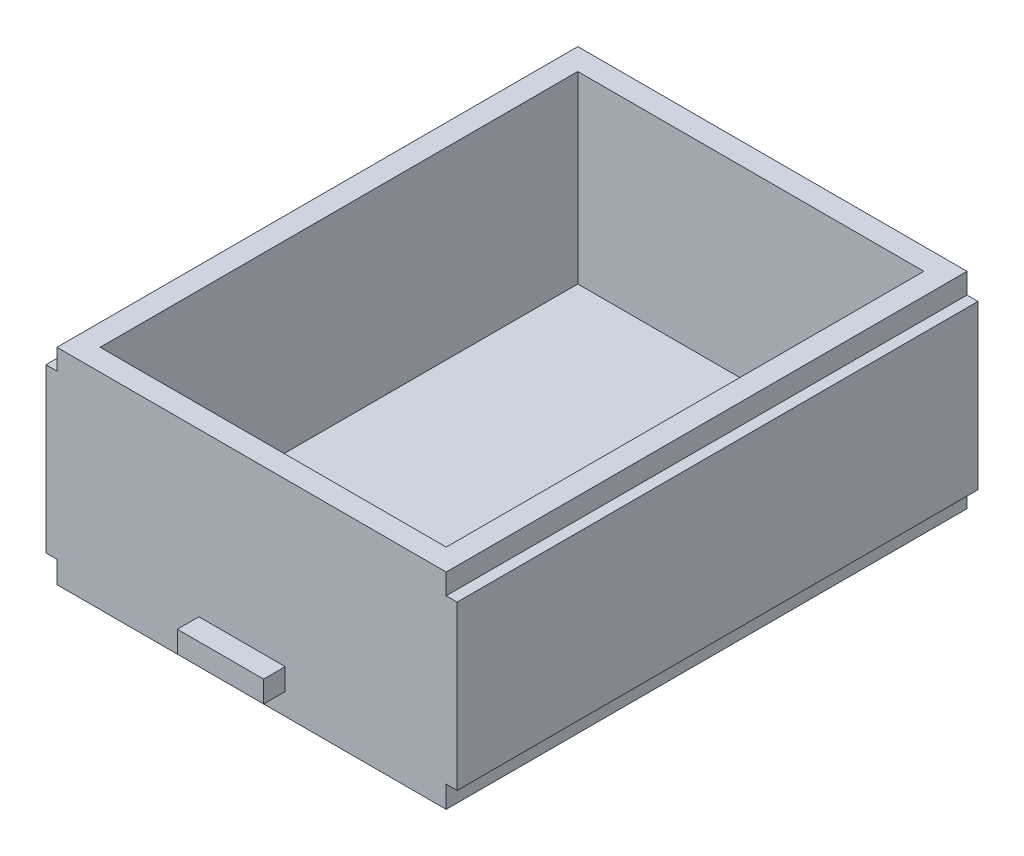
SolidWorks part; units mm, degrees
ref_plane "Alzado" through (0, 0, 0) normal (0, 0, 1) x (1, 0, 0)
ref_plane "Planta" through (0, 0, 0) normal (0, 1, 0) x (1, 0, 0)
ref_plane "Vista lateral" through (0, 0, 0) normal (1, 0, 0) x (0, 0, -1)
sketch "Croquis1" plane through (0, 0, 0) normal (0, 0, 1) x (1, 0, 0)
  line L1 (36.068, -19.05) -> (-36.068, -19.05)
  line L2 (36.068, -19.05) -> (36.068, 19.05)
  line L3 (36.068, 19.05) -> (-36.068, 19.05)
  line L4 (-36.068, -19.05) -> (-36.068, 19.05)
  line L5 (36.068, -19.05) -> (-36.068, 19.05) construction
  line L6 (36.068, 19.05) -> (-36.068, -19.05) construction
  point P0 (0, 0)
  dimension "D1" = 72.136
  dimension "D2" = 38.1
extrude "Saliente-Extruir1" add sketch "Croquis1" along normal blind 96.52
shell "Vaciado1" thickness 4
sketch "Croquis2" plane through (0, 0, 96.52) normal (0, 0, 1) x (1, 0, 0)
  line L0 (-36.068, 19.05) -> (-36.068, -19.05) construction
  line L1 (-36.068, 15.24) -> (-38.1, 15.24)
  line L2 (-36.068, 15.24) -> (-36.068, -14.986)
  line L3 (-36.068, -14.986) -> (-38.1, -14.986)
  line L4 (-38.1, 15.24) -> (-38.1, -14.986)
  line L5 (36.068, 19.05) -> (-36.068, 19.05) construction
  line L6 (0, 19.05) -> (0, -19.05) construction
  line L7 (-36.068, -19.05) -> (36.068, -19.05) construction
  line L8 (36.068, -14.986) -> (38.1, -14.986)
  line L9 (38.1, 15.24) -> (38.1, -14.986)
  line L10 (36.068, 15.24) -> (38.1, 15.24)
  line L11 (36.068, 15.24) -> (36.068, -14.986)
  dimension "D1" = 2.032
  dimension "D2" = 3.81
  dimension "D3" = 30.226
extrude "Saliente-Extruir2" add sketch "Croquis2" against normal blind 96.52
sketch "Croquis3" plane through (0, 0, 96.52) normal (0, 0, 1) x (1, 0, 0)
  line L0 (-36.068, -19.05) -> (36.068, -19.05) construction
  line L1 (6.2297, -15.05) -> (-9.7703, -15.05)
  line L2 (6.2297, -15.05) -> (6.2297, -11.05)
  line L3 (6.2297, -11.05) -> (-9.7703, -11.05)
  line L4 (-9.7703, -15.05) -> (-9.7703, -11.05)
  line L5 (6.2297, -15.05) -> (-9.7703, -11.05) construction
  line L6 (6.2297, -11.05) -> (-9.7703, -15.05) construction
  point P0 (-1.7703, -13.05)
  dimension "D1" = 16
  dimension "D2" = 4
  dimension "D3" = 4
extrude "Saliente-Extruir3" add sketch "Croquis3" along normal blind 4
